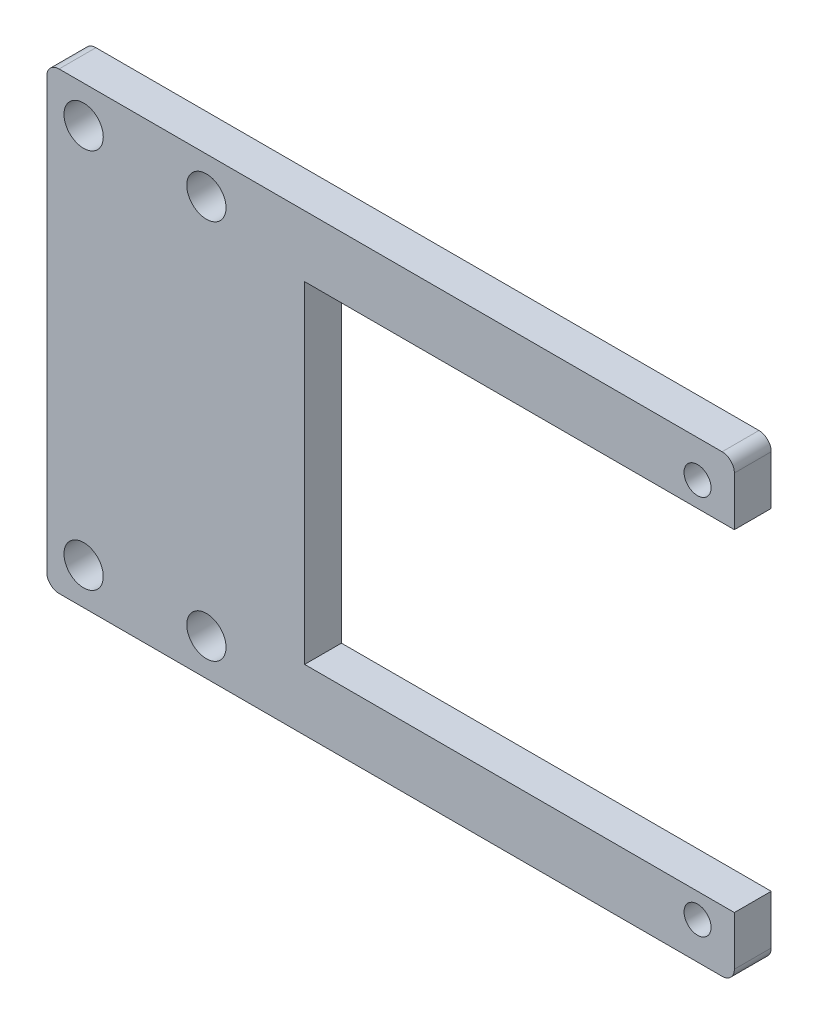
SolidWorks part; units mm, degrees
ref_plane "前视基准面" through (0, 0, 0) normal (0, 0, 1) x (1, 0, 0)
ref_plane "上视基准面" through (0, 0, 0) normal (0, 1, 0) x (1, 0, 0)
ref_plane "右视基准面" through (0, 0, 0) normal (1, 0, 0) x (0, 0, -1)
other "Configuration Table"
sketch "草图2" plane through (0, 0, 0) normal (0, 0, 1) x (1, 0, 0)
  line L0 (28, 18.5) -> (28, 13.5)
  line L1 (-28, -18.5) -> (28, -18.5)
  line L2 (-28, -18.5) -> (-28, 18.5)
  line L3 (-28, 18.5) -> (28, 18.5)
  line L4 (28, -18.5) -> (28, 18.5) construction
  line L5 (-28, -18.5) -> (28, 18.5) construction
  line L6 (-28, 18.5) -> (28, -18.5) construction
  line L7 (28, 13.5) -> (-7, 13.5)
  line L8 (-7, 13.5) -> (-7, -13.5)
  line L9 (-7, -13.5) -> (28, -13.5)
  line L10 (28, -13.5) -> (28, -18.5)
  line L11 (-43.4098, 0) -> (44.1083, 0) construction
  line L13 (-28, 18.5) -> (-7, 18.5) construction
  line L14 (-28, 18.5) -> (-28, 12.5) construction
  line L15 (-28, 12.5) -> (-7, 12.5) construction
  line L16 (-7, 18.5) -> (-7, 12.5) construction
  circle A0 centre (25, 15.5) radius 1.1
  circle A2 centre (25, -15.5) radius 1.1
  circle A3 centre (-25, 15.5) radius 1.6
  circle A4 centre (-15, 15.5) radius 1.6
  circle A5 centre (-15, -15.5) radius 1.6
  circle A6 centre (-25, -15.5) radius 1.6
  point P0 (0, 0)
  point P21 (-25, 11.5969)
  point P23 (0, 0)
  point P24 (-25, 14.9318)
  point P26 (-13.1914, 15.5)
  point P27 (0, 0)
  dimension "D6" = 2.2
  dimension "D7" = 6
  dimension "D10" = 21
  dimension "D11" = 3.2
  dimension "D14" = 8
  dimension "D15" = 3.2
  dimension "D16" = 10
  dimension "D1" = 37
  dimension "D2" = 56
  dimension "D3" = 5
  dimension "D4" = 5
  dimension "D5" = 35
  dimension "D8" = 3
  dimension "D9" = 3
  dimension "D12" = 3
  dimension "D13" = 3
extrude "凸台-拉伸1" add sketch "草图2" along normal blind 3
fillet "圆角1" radius 1 4 edges at (-28, -18.5, 1.5) (28, -18.5, 1.5) (28, 18.5, 1.5) (-28, 18.5, 1.5)
